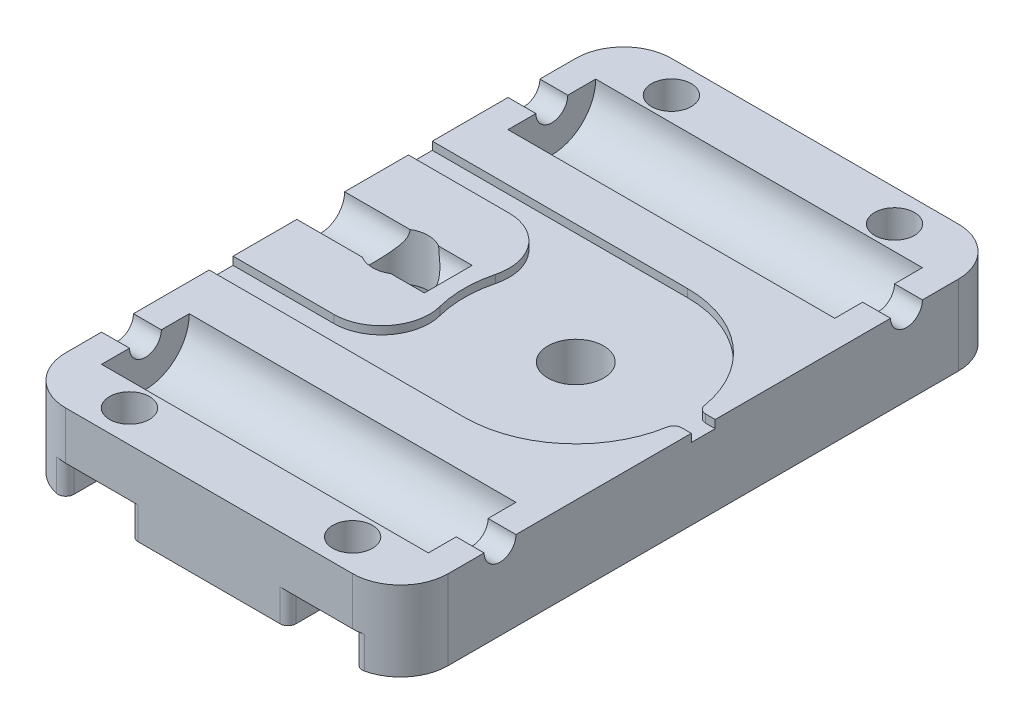
SolidWorks part; units mm, degrees
ref_plane "Спереди" through (0, 0, 0) normal (0, 0, 1) x (1, 0, 0)
ref_plane "Сверху" through (0, 0, 0) normal (0, 1, 0) x (1, 0, 0)
ref_plane "Справа" through (0, 0, 0) normal (1, 0, 0) x (0, 0, -1)
sketch "Эскиз1" plane through (0, 0, 0) normal (0, 1, 0) x (1, 0, 0)
  line L1 (-12, 19) -> (12, 19)
  line L2 (-12, 19) -> (-12, -19)
  line L3 (-12, -19) -> (12, -19)
  line L4 (12, 19) -> (12, -19)
  line L5 (-12, 19) -> (12, -19) construction
  line L6 (-12, -19) -> (12, 19) construction
  point P0 (0, 0)
  dimension "D1" = 38
  dimension "D2" = 24
extrude "Бобышка-Вытянуть1" add sketch "Эскиз1" along normal blind 5
sketch "Эскиз2" plane through (0, 0, 0) normal (1, 0, 0) x (0, 0, -1)
  line L0 (-19, 5) -> (19, 5) construction
  line L1 (0, 0) -> (0, 19.0603) construction
  line L2 (-10, 5) -> (10, 5) construction
  circle A0 centre (-12.75, 5) radius 2.75
  circle A1 centre (12.75, 5) radius 2.75
  dimension "D1" = 5.5
  dimension "D2" = 20
extrude "Вырез-Вытянуть1" cut sketch "Эскиз2" against normal mid plane 20.5
sketch "Эскиз3" plane through (0, 0, 0) normal (1, 0, 0) x (0, 0, -1)
  circle A0 centre (-12.75, 5) radius 1
  circle A1 centre (12.75, 5) radius 1
  arc A2 (10, 5) -> (15.5, 5) centre (12.75, 5) ccw construction
  arc A3 (-15.5, 5) -> (-10, 5) centre (-12.75, 5) ccw construction
  dimension "D1" = 2
  dimension "D2" = 2
extrude "Вырез-Вытянуть2" cut sketch "Эскиз3" against normal through all both and the other way through all
sketch "Эскиз4" plane through (0, 5, 0) normal (0, 1, 0) x (1, 0, 0)
  line L0 (12, -11.75) -> (12, 11.75) construction
  line L1 (4, 7) -> (-12, 7)
  line L2 (-12, 11.75) -> (-12, -11.75) construction
  line L3 (-12, 7) -> (-12, 5.5)
  line L4 (-12, 5.5) -> (-0.3301, 5.5)
  line L5 (10.9597, 0.75) -> (12, 0.75)
  line L6 (12, 0.75) -> (12, -0.75)
  line L7 (12, -0.75) -> (10.9597, -0.75)
  line L8 (11, 0) -> (12, 0) construction
  line L9 (4, 0) -> (-12, 0) construction
  line L10 (-12, -7) -> (-12, -5.5)
  line L11 (-12, -5.5) -> (-0.3301, -5.5)
  line L12 (4, -7) -> (-12, -7)
  arc A0 (-0.3301, 5.5) -> (-0.3301, -5.5) centre (4, 0) ccw
  arc A1 (4, 7) -> (-0.3301, 5.5) centre (4, 0) ccw construction
  arc A2 (10.9597, 0.75) -> (4, 7) centre (4, 0) ccw
  arc A3 (11, 0) -> (10.9597, 0.75) centre (4, 0) ccw construction
  arc A4 (10.9597, -0.75) -> (11, 0) centre (4, 0) ccw construction
  arc A5 (4, -7) -> (10.9597, -0.75) centre (4, 0) ccw
  arc A6 (-0.3301, -5.5) -> (4, -7) centre (4, 0) ccw construction
  dimension "D2" = 14
  dimension "D1" = 8
  dimension "D3" = 1.5
  dimension "D4" = 1.5
extrude "Вырез-Вытянуть3" cut sketch "Эскиз4" against normal blind 0.5
sketch "Эскиз5" plane through (0, 5, 0) normal (0, 1, 0) x (1, 0, 0)
  line L0 (-12, 5.5) -> (-12, -5.5) construction
  circle A0 centre (4, 0) radius 1.75
  circle A1 centre (-7, 0) radius 1.75
  dimension "D1" = 3.5
  dimension "D2" = 3.5
  dimension "D3" = 5
extrude "Вырез-Вытянуть4" cut sketch "Эскиз5" against normal through all
fillet "Скругление1" radius 3 2 edges at (-0.3301, 4.75, 5.5) (-0.3301, 4.75, -5.5)
fillet "Скругление2" radius 3 4 edges at (-12, 2.5, -19) (12, 2.5, -19) (-12, 2.5, 19) (12, 2.5, 19)
sketch "Эскиз6" plane through (-12, 0, 0) normal (-1, 0, 0) x (0, 0, 1)
  line L0 (-5.5, 5) -> (5.5, 5) construction
  circle A0 centre (0, 5) radius 1.5
  dimension "D1" = 3
extrude "Вырез-Вытянуть5" cut sketch "Эскиз6" against normal blind 8
fillet "Скругление3" radius 0.5 2 edges at (10.9597, 4.75, 0.75) (10.9597, 4.75, -0.75)
sketch "Эскиз7" plane through (0, 5, 0) normal (0, 1, 0) x (1, 0, 0)
  line L0 (-9, -19) -> (9, -19) construction
  line L1 (7, 17) -> (-7, 17) construction
  line L2 (7, 17) -> (7, -17) construction
  line L3 (7, -17) -> (-7, -17) construction
  line L4 (-7, 17) -> (-7, -17) construction
  line L5 (7, 17) -> (-7, -17) construction
  line L6 (7, -17) -> (-7, 17) construction
  circle A0 centre (-7, 17) radius 1.25
  circle A1 centre (7, 17) radius 1.25
  circle A2 centre (7, -17) radius 1.25
  circle A3 centre (-7, -17) radius 1.25
  point P0 (0, 0)
  dimension "D1" = 2
  dimension "D2" = 14
  dimension "D3" = 2.5
  dimension "D4" = 2.5
  dimension "D5" = 2.5
  dimension "D6" = 2.5
extrude "Вырез-Вытянуть6" cut sketch "Эскиз7" against normal through all
sketch "Эскиз8" plane through (0, 0, 0) normal (0, -1, 0) x (1, 0, 0)
  circle A0 centre (4, 0) radius 3
  circle A1 centre (-7, 0) radius 3
  dimension "D1" = 6
  dimension "D2" = 6
extrude "Вырез-Вытянуть7" cut sketch "Эскиз8" against normal offset from surface (2 mm away) 3 up to face at (2.4808, 5, -7.7127)
sketch "Эскиз9" plane through (0, 0, 0) normal (0, -1, 0) x (1, 0, 0)
  line L0 (-9.05, 17) -> (-9.05, 20)
  line L1 (-9.05, 20) -> (-4.95, 20)
  line L2 (-4.95, 20) -> (-4.95, 17)
  line L3 (0, 19) -> (0, -19) construction
  line L4 (-9, 19) -> (9, 19) construction
  line L5 (9, -19) -> (-9, -19) construction
  line L6 (0, 0) -> (12, 0) construction
  line L7 (12, 16) -> (12, -16) construction
  line L8 (9.05, 17) -> (9.05, 20)
  line L9 (9.05, 20) -> (4.95, 20)
  line L10 (4.95, 20) -> (4.95, 17)
  line L11 (4.95, -20) -> (4.95, -17)
  line L12 (9.05, -20) -> (4.95, -20)
  line L13 (9.05, -17) -> (9.05, -20)
  line L14 (-9.05, -17) -> (-9.05, -20)
  line L15 (-9.05, -20) -> (-4.95, -20)
  line L16 (-4.95, -20) -> (-4.95, -17)
  arc A0 (-9.05, 17) -> (-4.95, 17) centre (-7, 17) ccw
  arc A1 (-4.95, 17) -> (-9.05, 17) centre (-7, 17) ccw construction
  arc A2 (9.05, 17) -> (4.95, 17) centre (7, 17) cw
  arc A3 (9.05, -17) -> (4.95, -17) centre (7, -17) ccw
  arc A4 (-9.05, -17) -> (-4.95, -17) centre (-7, -17) cw
  dimension "D1" = 4.1
  dimension "D2" = 3
extrude "Вырез-Вытянуть8" cut sketch "Эскиз9" against normal offset from surface (2 mm away) 3 up to face at (-7, 5, 18.25)
fillet "Скругление4" radius 0.5 8 edges at (9.05, 1, -18.9996) (4.95, 1, -19) (-9.05, 1, -18.9996) (-4.95, 1, -19) (9.05, 1, 18.9996) (4.95, 1, 19) (-4.95, 1, 19) (-9.05, 1, 18.9996)
equation "\"Ball_bearing_D\"= 12.7"
equation "\"Ball_bearing_h1\"= 9"
equation "\"Ball_bearing_d1\"= 5.9"
equation "\"Ball_bearing_d2\"= 18"
equation "\"Ball_bearing_h2\"= 6.6"
equation "\"Brake_tube_d1\"= 2"
equation "\"Brake_tube_d2\"= 5"
equation "\"Brake_tube_h\"= 20"
equation "\"print_offset\"= 0.5"
equation "\"D1@Эскиз2\"=\"print_offset\"+\"Brake_tube_d2\""
equation "\"D1@Вырез-Вытянуть1\"=\"Brake_tube_h\"+\"print_offset\""
equation "\"D1@Эскиз3\"=\"Brake_tube_d1\""
equation "\"D2@Эскиз3\"=\"D1@Эскиз3\""
equation "\"inner_distance\"= 20"
equation "\"D2@Эскиз2\"=\"inner_distance\""
equation "\"D1@Эскиз1\"=\"inner_distance\"+\"Brake_tube_d2\"*2+8"
equation "\"D4@Эскиз4\"=\"D3@Эскиз4\""
equation "\"D1@Эскиз5\"=\"print_offset\"+3"
equation "\"D2@Эскиз5\"=\"D1@Эскиз5\""
equation "\"D2@Эскиз1\"=\"Brake_tube_h\"+4"
equation "\"D4@Эскиз7\"=\"D3@Эскиз7\""
equation "\"D5@Эскиз7\"=\"D3@Эскиз7\""
equation "\"D6@Эскиз7\"=\"D3@Эскиз7\""
equation "\"D2@Эскиз8\"=\"D1@Эскиз8\""
